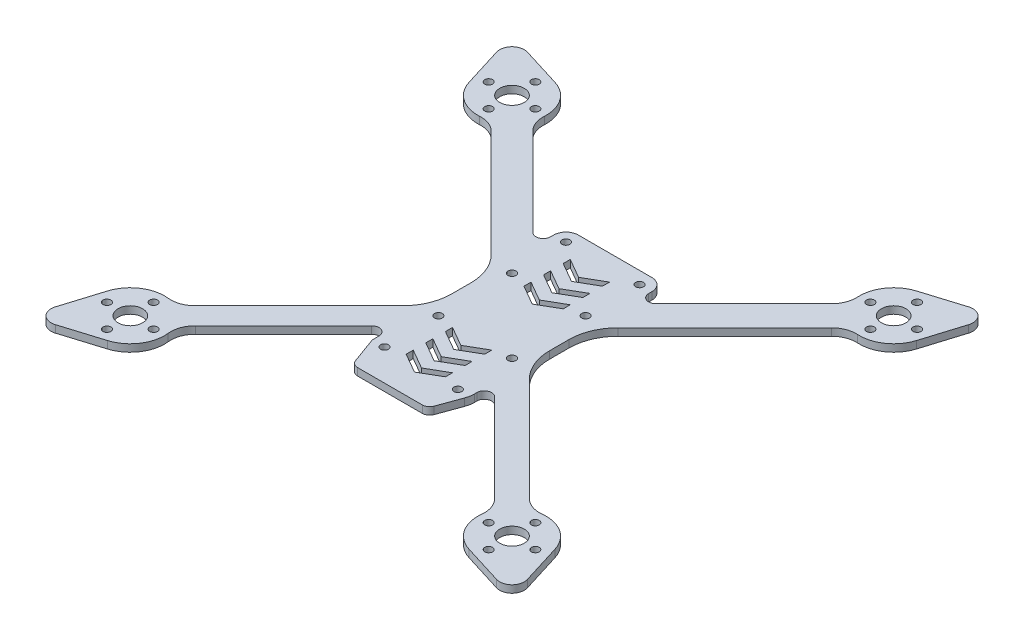
SolidWorks part; units mm, degrees
ref_plane "Front Plane" through (0, 0, 0) normal (0, 0, 1) x (1, 0, 0)
ref_plane "Top Plane" through (0, 0, 0) normal (0, 1, 0) x (1, 0, 0)
ref_plane "Right Plane" through (0, 0, 0) normal (1, 0, 0) x (0, 0, -1)
sketch "Sketch1" plane through (0, 0, 0) normal (0, 1, 0) x (1, 0, 0)
  line L0 (0, 110) -> (0, -110) construction
  line L3 (19.341, -38.6569) -> (16.0219, -47.7761)
  line L4 (-15, 42) -> (15, 42)
  line L7 (20, 3.2304) -> (20, -4.6447)
  line L8 (-15, 15) -> (15, 15) construction
  line L10 (-15, -15) -> (15, -15) construction
  line L11 (15, 15) -> (15, -15) construction
  line L12 (25.1213, 33.6066) -> (60.89, 69.3753)
  line L13 (25.8579, 17.3726) -> (69.3753, 60.89)
  line L14 (25.0654, -32.1365) -> (60.9986, -68.0696)
  line L15 (25.8579, -18.7868) -> (68.0696, -60.9986)
  line L16 (77.7817, 77.7817) -> (98.9949, 98.9949) construction
  line L17 (77.7817, -77.7817) -> (98.9949, -98.9949) construction
  line L18 (73.6461, -91.157) -> (89.9418, -96.1957)
  line L19 (96.1957, -89.9418) -> (91.157, -73.6461)
  line L20 (89.9418, 96.1957) -> (73.6461, 91.157)
  line L21 (96.1957, 89.9418) -> (91.157, 73.6461)
  line L22 (0, 0) -> (77.7817, 77.7817) construction
  line L23 (20, 37) -> (20, 35.7279)
  line L24 (0, 0) -> (77.7817, -77.7817) construction
  line L35 (-20, 0) -> (20, 0) construction
  line L37 (19.9441, -34.2578) -> (19.9441, -35.2367)
  line L38 (-19.9441, -37) -> (-16.0219, -47.7761)
  line L39 (0, 0) -> (-77.7817, -77.7817) construction
  line L40 (0, 0) -> (-77.7817, 77.7817) construction
  line L41 (-77.7817, -77.7817) -> (-98.9949, -98.9949) construction
  line L42 (-77.7817, 77.7817) -> (-98.9949, 98.9949) construction
  line L43 (-15, 15) -> (-15, -15) construction
  line L46 (-19.9441, -34.2578) -> (-19.9441, -37)
  line L47 (-20, 37) -> (-20, 35.7279)
  line L48 (-96.1957, 89.9418) -> (-91.157, 73.6461)
  line L49 (-89.9418, 96.1957) -> (-73.6461, 91.157)
  line L50 (-96.1957, -89.9418) -> (-91.157, -73.6461)
  line L51 (-73.6461, -91.157) -> (-89.9418, -96.1957)
  line L52 (-25.8579, -18.7868) -> (-68.0696, -60.9986)
  line L53 (-25.0654, -32.1365) -> (-60.9986, -68.0696)
  line L54 (-25.8579, 17.3726) -> (-69.3753, 60.89)
  line L55 (-25.1213, 33.6066) -> (-60.89, 69.3753)
  line L56 (-20, 3.2304) -> (-20, -4.6447)
  line L57 (-17.3809, -42) -> (-15.5516, -47.0261) construction
  line L58 (15.5516, -47.0261) -> (17.3809, -42) construction
  line L59 (-13.2028, -49.75) -> (13.2028, -49.75)
  circle A1 centre (77.7817, 77.7817) radius 63.5 construction
  circle A2 centre (77.7817, -77.7817) radius 63.5 construction
  circle A5 centre (77.7817, 77.7817) radius 9.5 construction
  circle A9 centre (77.7817, 68.2817) radius 1.6
  circle A10 centre (68.2817, 77.7817) radius 1.6
  circle A11 centre (77.7817, 87.2817) radius 1.6
  circle A12 centre (87.2817, 77.7817) radius 1.6
  circle A13 centre (77.7817, -87.2817) radius 1.6
  circle A14 centre (77.7817, -77.7817) radius 9.5 construction
  circle A15 centre (68.2817, -77.7817) radius 1.6
  circle A16 centre (77.7817, -68.2817) radius 1.6
  circle A17 centre (87.2817, -77.7817) radius 1.6
  arc A28 (77.0028, 63.8034) -> (91.157, 73.6461) centre (77.7817, 77.7817) ccw
  arc A29 (63.8668, -76.2411) -> (73.6461, -91.157) centre (77.7817, -77.7817) ccw
  arc A30 (73.6461, 91.157) -> (63.8034, 77.0028) centre (77.7817, 77.7817) ccw
  arc A31 (91.157, -73.6461) -> (76.2411, -63.8668) centre (77.7817, -77.7817) ccw
  arc A36 (96.1957, 89.9418) -> (89.9418, 96.1957) centre (91.4188, 91.4188) ccw
  arc A37 (96.1957, -89.9418) -> (89.9418, -96.1957) centre (91.4188, -91.4188) cw
  circle A42 centre (15, 15) radius 1.6
  circle A43 centre (15, -15) radius 1.6
  circle A44 centre (77.7817, 77.7817) radius 5
  circle A45 centre (77.7817, -77.7817) radius 5
  circle A47 centre (0, 0) radius 110 construction
  circle A49 centre (-87.2817, -77.7817) radius 1.6 [skipped]
  circle A50 centre (-77.7817, -68.2817) radius 1.6 [skipped]
  circle A51 centre (-68.2817, -77.7817) radius 1.6 [skipped]
  circle A52 centre (-77.7817, -87.2817) radius 1.6 [skipped]
  circle A53 centre (-77.7817, 87.2817) radius 1.6 [skipped]
  circle A54 centre (-68.2817, 77.7817) radius 1.6 [skipped]
  circle A55 centre (-77.7817, 68.2817) radius 1.6 [skipped]
  circle A56 centre (-87.2817, 77.7817) radius 1.6 [skipped]
  circle A57 centre (-77.7817, -77.7817) radius 9.5 construction
  circle A58 centre (-77.7817, 77.7817) radius 9.5 construction
  circle A91 centre (14.9441, -37) radius 1.6
  circle A92 centre (15, 37) radius 1.6
  arc A97 (60.89, 69.3753) -> (63.8034, 77.0028) centre (53.8189, 76.4463) ccw
  arc A98 (69.3753, 60.89) -> (77.0028, 63.8034) centre (76.4463, 53.8189) cw
  arc A99 (63.8668, -76.2411) -> (60.9986, -68.0696) centre (53.9275, -75.1407) ccw
  arc A100 (68.0696, -60.9986) -> (76.2411, -63.8668) centre (75.1407, -53.9275) ccw
  circle A103 centre (-77.7817, -77.7817) radius 9.5 construction
  circle A104 centre (-77.7817, 77.7817) radius 9.5 construction
  circle A105 centre (-77.7817, -77.7817) radius 63.5 construction
  circle A106 centre (-77.7817, 77.7817) radius 63.5 construction
  arc A107 (-68.0696, -60.9986) -> (-76.2411, -63.8668) centre (-75.1407, -53.9275) cw
  arc A108 (-63.8668, -76.2411) -> (-60.9986, -68.0696) centre (-53.9275, -75.1407) cw
  arc A109 (-69.3753, 60.89) -> (-77.0028, 63.8034) centre (-76.4463, 53.8189) ccw
  arc A110 (-60.89, 69.3753) -> (-63.8034, 77.0028) centre (-53.8189, 76.4463) cw
  circle A111 centre (-15, 37) radius 1.6
  circle A112 centre (-14.9441, -37) radius 1.6
  circle A113 centre (-77.7817, -77.7817) radius 5
  circle A114 centre (-77.7817, 77.7817) radius 5
  circle A115 centre (-15, -15) radius 1.6
  circle A116 centre (-15, 15) radius 1.6
  arc A117 (-96.1957, -89.9418) -> (-89.9418, -96.1957) centre (-91.4188, -91.4188) ccw
  arc A118 (-96.1957, 89.9418) -> (-89.9418, 96.1957) centre (-91.4188, 91.4188) cw
  arc A119 (-91.157, -73.6461) -> (-76.2411, -63.8668) centre (-77.7817, -77.7817) cw
  arc A120 (-73.6461, 91.157) -> (-63.8034, 77.0028) centre (-77.7817, 77.7817) cw
  arc A121 (-63.8668, -76.2411) -> (-73.6461, -91.157) centre (-77.7817, -77.7817) cw
  arc A122 (-77.0028, 63.8034) -> (-91.157, 73.6461) centre (-77.7817, 77.7817) cw
  circle A123 centre (-87.2817, -77.7817) radius 1.6
  circle A124 centre (-77.7817, -68.2817) radius 1.6
  circle A125 centre (-68.2817, -77.7817) radius 1.6
  circle A126 centre (-77.7817, -87.2817) radius 1.6
  circle A127 centre (-87.2817, 77.7817) radius 1.6
  circle A128 centre (-77.7817, 87.2817) radius 1.6
  circle A129 centre (-68.2817, 77.7817) radius 1.6
  circle A130 centre (-77.7817, 68.2817) radius 1.6
  arc A131 (20, 35.7279) -> (25.1213, 33.6066) centre (23, 35.7279) ccw
  arc A132 (25.0654, -32.1365) -> (19.9441, -34.2578) centre (22.9441, -34.2578) ccw
  arc A133 (-25.8579, -18.7868) -> (-20, -4.6447) centre (-40, -4.6447) ccw
  arc A134 (-25.8579, 17.3726) -> (-20, 3.2304) centre (-40, 3.2304) cw
  arc A135 (25.8579, -18.7868) -> (20, -4.6447) centre (40, -4.6447) cw
  arc A136 (25.8579, 17.3726) -> (20, 3.2304) centre (40, 3.2304) ccw
  arc A137 (-19.9441, -34.2578) -> (-25.0654, -32.1365) centre (-22.9441, -34.2578) ccw
  arc A138 (-20, 35.7279) -> (-25.1213, 33.6066) centre (-23, 35.7279) cw
  arc A141 (15, 42) -> (20, 37) centre (15, 37) cw
  arc A142 (-20, 37) -> (-15, 42) centre (-15, 37) cw
  arc A143 (-16.0219, -47.7761) -> (-13.2028, -49.75) centre (-13.2028, -46.75) ccw
  arc A144 (13.2028, -49.75) -> (16.0219, -47.7761) centre (13.2028, -46.75) ccw
  arc A145 (19.9441, -35.2367) -> (19.341, -38.6569) centre (9.9441, -35.2367) cw
  point P4 (0, 15)
  point P6 (0, 15)
  point P12 (0, 38)
  point P34 (77.7817, 77.7817)
  point P49 (0, -15)
  point P50 (0, 15)
  point P65 (0, 0)
  point P75 (-77.7817, 77.7817)
  point P76 (0, 42)
  point P80 (0, -15)
  point P89 (0, 38)
  point P93 (0, -15)
  point P160 (0, -38)
  point P165 (0, -42)
  point P168 (20, 28.4853)
  point P171 (19.9441, -27.0152)
  point P178 (-20, -12.9289)
  point P180 (0, -38)
  point P182 (-20, 11.5147)
  point P185 (20, -12.9289)
  point P188 (20, 11.5147)
  point P190 (-19.9441, -27.0152)
  point P193 (-20, 28.4853)
  point P196 (-19.9441, -42)
  point P199 (19.9441, -42)
  point P202 (20, 42)
  point P205 (-20, 42)
  dimension "D3" = 42
  dimension "D9" = 4
  dimension "D13" = 20
  dimension "D17" = 10
  dimension "D18" = 5
  dimension "D19" = 12.75
  dimension "D5" = 5
  dimension "D6" = 5
  dimension "D7" = 6
  dimension "D8" = 6
  dimension "D11" = 3
  dimension "D12" = 10
  dimension "D14" = 3
  dimension "D4" = 3
  dimension "D2" = 20
  dimension "D15" = 30
  dimension "D16" = 30
  dimension "D10" = 4
extrude "Boss-Extrude1" add sketch "Sketch1" along normal blind 3
sketch "Sketch2" plane through (0, 0, 0) normal (0, -1, 0) x (1, 0, 0)
  line L0 (0, -42) -> (0, 49.75) construction
  line L1 (15, -42) -> (-15, -42) construction
  line L2 (-13.2028, 49.75) -> (13.2028, 49.75) construction
  line L3 (-8, 35.1312) -> (0, 39.75)
  line L4 (0, 39.75) -> (8, 35.1312)
  line L6 (8, 32.2444) -> (0, 36.8632)
  line L7 (0, 36.8632) -> (-8, 32.2444)
  line L8 (-8, 32.2444) -> (-8, 35.1312)
  line L9 (8, 32.2444) -> (8, 35.1312)
  line L10 (-8, 27.1312) -> (0, 31.75)
  line L11 (0, 31.75) -> (8, 27.1312)
  line L12 (8, 24.2444) -> (0, 28.8632)
  line L13 (0, 28.8632) -> (-8, 24.2444)
  line L14 (-8, 24.2444) -> (-8, 27.1312)
  line L15 (8, 24.2444) -> (8, 27.1312)
  line L16 (-8, 19.1312) -> (0, 23.75)
  line L17 (0, 23.75) -> (8, 19.1312)
  line L18 (8, 16.2444) -> (0, 20.8632)
  line L19 (0, 20.8632) -> (-8, 16.2444)
  line L20 (-8, 16.2444) -> (-8, 19.1312)
  line L21 (8, 16.2444) -> (8, 19.1312)
  line L40 (-8, -12.8688) -> (0, -8.25)
  line L41 (0, -8.25) -> (8, -12.8688)
  line L42 (8, -15.7556) -> (0, -11.1368)
  line L43 (0, -11.1368) -> (-8, -15.7556)
  line L44 (-8, -15.7556) -> (-8, -12.8688)
  line L45 (8, -15.7556) -> (8, -12.8688)
  line L46 (-8, -20.8688) -> (0, -16.25)
  line L47 (0, -16.25) -> (8, -20.8688)
  line L48 (8, -23.7556) -> (0, -19.1368)
  line L49 (0, -19.1368) -> (-8, -23.7556)
  line L50 (-8, -23.7556) -> (-8, -20.8688)
  line L51 (8, -23.7556) -> (8, -20.8688)
  line L52 (-8, -28.8688) -> (0, -24.25)
  line L53 (0, -24.25) -> (8, -28.8688)
  line L54 (8, -31.7556) -> (0, -27.1368)
  line L55 (0, -27.1368) -> (-8, -31.7556)
  line L56 (-8, -31.7556) -> (-8, -28.8688)
  line L57 (8, -31.7556) -> (8, -28.8688)
  line L58 (-8, 11.1312) -> (0, 15.75) [skipped]
  line L59 (0, 15.75) -> (8, 11.1312) [skipped]
  line L60 (8, 8.2444) -> (0, 12.8632) [skipped]
  line L61 (0, 12.8632) -> (-8, 8.2444) [skipped]
  line L62 (-8, 8.2444) -> (-8, 11.1312) [skipped]
  line L63 (8, 8.2444) -> (8, 11.1312) [skipped]
  line L64 (-8, 3.1312) -> (0, 7.75) [skipped]
  line L65 (0, 7.75) -> (8, 3.1312) [skipped]
  line L66 (8, 0.2444) -> (0, 4.8632) [skipped]
  line L67 (0, 4.8632) -> (-8, 0.2444) [skipped]
  line L68 (-8, 0.2444) -> (-8, 3.1312) [skipped]
  line L69 (8, 0.2444) -> (8, 3.1312) [skipped]
  line L70 (-8, -4.8688) -> (0, -0.25) [skipped]
  line L71 (0, -0.25) -> (8, -4.8688) [skipped]
  line L72 (0, -3.1368) -> (-8, -7.7556) [skipped]
  line L73 (8, -7.7556) -> (0, -3.1368) [skipped]
  line L74 (-8, -7.7556) -> (-8, -4.8688) [skipped]
  line L75 (8, -7.7556) -> (8, -4.8688) [skipped]
  dimension "D1" = 8
  dimension "D2" = 8
  dimension "D3" = 2.5
  dimension "D4" = 10
  dimension "D5" = 120
  dimension "D6" = 60
  dimension "D7" = 9
extrude "Cut-Extrude1" cut sketch "Sketch2" against normal through all
